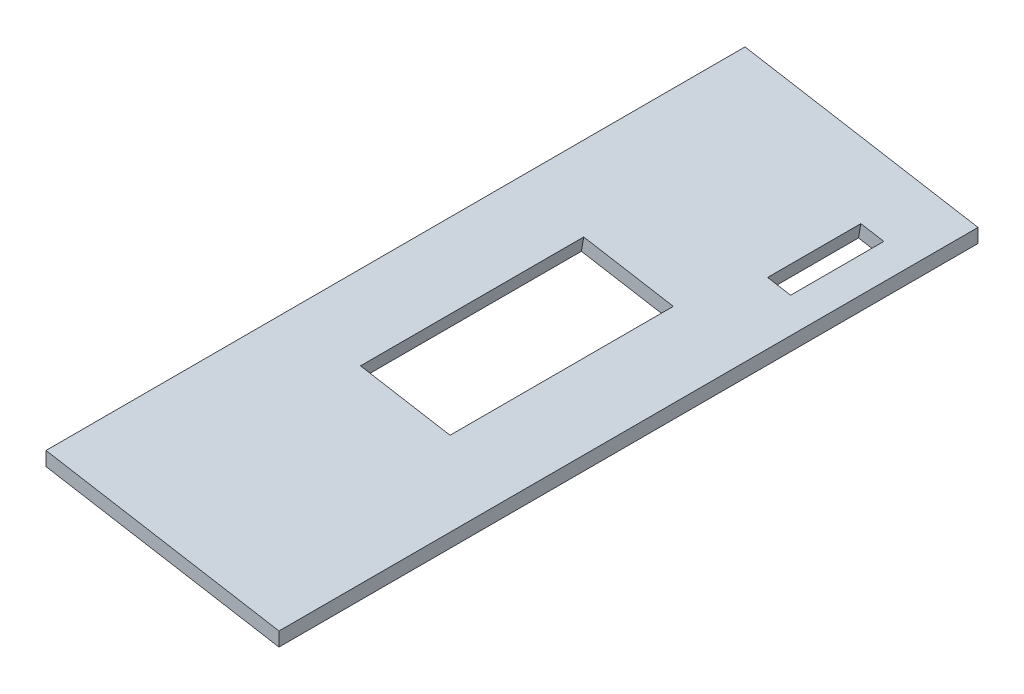
SolidWorks part; units mm, degrees
material "CA"
ref_plane "Front Plane" through (0, 0, 0) normal (0, 0, 1) x (1, 0, 0)
ref_plane "Top Plane" through (0, 0, 0) normal (0, 1, 0) x (1, 0, 0)
ref_plane "Right Plane" through (0, 0, 0) normal (1, 0, 0) x (0, 0, -1)
sketch "Sketch2" plane through (0, 0, 0) normal (0, 0, 1) x (1, 0, 0)
  line L0 (68.2048, -44.5237) -> (68.2048, -38.5237)
  line L1 (68.2048, -38.5237) -> (-31.7952, -21.4304)
  line L2 (-31.7952, -21.4304) -> (-31.7952, -27.4304)
  line L3 (-31.7952, -27.4304) -> (68.2048, -44.5237)
  line L4 (68.2048, -44.5237) -> (-11.8674, -44.5237) construction
  dimension "D1" = 9.7
  dimension "D2" = 100
extrude "Boss-Extrude1" add sketch "Sketch2" along normal blind 300
sketch "Sketch3" plane through (-4.4618, -26.1026, 0) normal (0.1685, 0.9857, 0) x (0.9857, -0.1685, 0)
  line L0 (73.7206, 0) -> (-27.7298, 0) construction
  line L1 (3.4954, -195.8) -> (42.4954, -195.8)
  line L2 (3.4954, -195.8) -> (3.4954, -100)
  line L3 (3.4954, -100) -> (42.4954, -100)
  line L4 (42.4954, -195.8) -> (42.4954, -100)
  line L5 (22.9954, -300) -> (22.9954, 0) construction
  line L6 (73.7206, -300) -> (-27.7298, -300) construction
  line L7 (22.9954, -100) -> (22.9954, -195.8) construction
  point P4 (22.9954, 0)
  dimension "D1" = 100
  dimension "D2" = 95.8
  dimension "D3" = 39
extrude "Cut-Extrude2" cut sketch "Sketch3" against normal blind 15
sketch "Sketch5" plane through (-4.4618, -26.1026, 0) normal (0.1685, 0.9857, 0) x (0.9857, -0.1685, 0)
  line L0 (73.7206, -300) -> (73.7206, 0) construction
  line L1 (50.7206, -27.6163) -> (60.7206, -27.6163)
  line L2 (50.7206, -27.6163) -> (50.7206, -67.6163)
  line L3 (50.7206, -67.6163) -> (60.7206, -67.6163)
  line L4 (60.7206, -27.6163) -> (60.7206, -67.6163)
  dimension "D1" = 40
  dimension "D2" = 10
  dimension "D3" = 13
extrude "Cut-Extrude3" cut sketch "Sketch5" against normal blind 10
